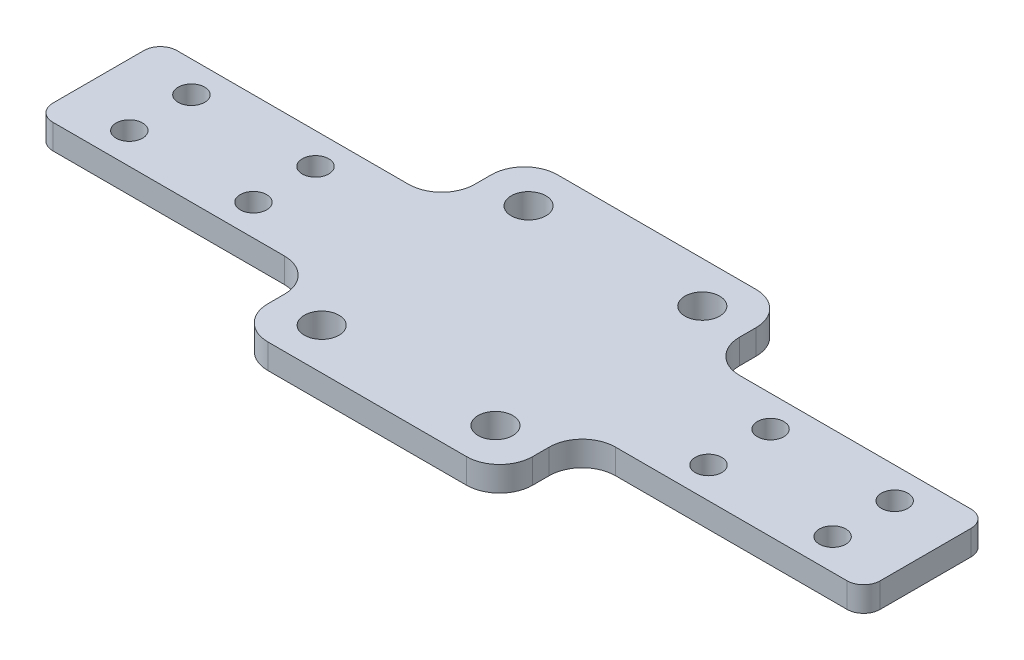
SolidWorks part; units mm, degrees
ref_plane "前视基准面" through (0, 0, 0) normal (0, 0, 1) x (1, 0, 0)
ref_plane "上视基准面" through (0, 0, 0) normal (0, 1, 0) x (1, 0, 0)
ref_plane "右视基准面" through (0, 0, 0) normal (1, 0, 0) x (0, 0, -1)
other "Configuration Table"
sketch "草图1" plane through (0, 0, 0) normal (0, 1, 0) x (1, 0, 0)
  line L1 (-50, -7.5) -> (50, -7.5)
  line L2 (-50, -7.5) -> (-50, 7.5)
  line L3 (-50, 7.5) -> (50, 7.5)
  line L4 (50, -7.5) -> (50, 7.5)
  line L5 (-50, -7.5) -> (50, 7.5) construction
  line L6 (-50, 7.5) -> (50, -7.5) construction
  point P0 (0, 0)
  dimension "D1" = 100
  dimension "D2" = 15
extrude "凸台-拉伸1" add sketch "草图1" along normal blind 3
sketch "草图2" plane through (0, 3, 0) normal (0, 1, 0) x (1, 0, 0)
  line L1 (-16, 17.5) -> (16, 17.5)
  line L2 (-16, 17.5) -> (-16, -17.5)
  line L3 (-16, -17.5) -> (16, -17.5)
  line L4 (16, 17.5) -> (16, -17.5)
  line L5 (0, 0) -> (0, 17.5) construction
  dimension "D1" = 32
  dimension "D2" = 35
  dimension "D3" = 17.5
extrude "凸台-拉伸2" add sketch "草图2" against normal blind 3
sketch "草图3" plane through (0, 3, 0) normal (0, 1, 0) x (1, 0, 0)
  line L0 (0, 0) -> (-50, 0) construction
  line L1 (-16, 7.5) -> (-50, 7.5) construction
  line L2 (0, 0) -> (0, 10) construction
  line L3 (-50, -7.5) -> (-16, -7.5) construction
  line L4 (-35, 7.5) -> (-35, -7.5) construction
  circle A0 centre (-42.5, 3.75) radius 1.6
  circle A1 centre (-42.5, -3.75) radius 1.6
  circle A2 centre (-27.5, -3.75) radius 1.6
  circle A3 centre (-27.5, 3.75) radius 1.6
  circle A4 centre (42.5, -3.75) radius 1.6
  circle A5 centre (42.5, 3.75) radius 1.6
  circle A6 centre (27.5, -3.75) radius 1.6
  circle A7 centre (27.5, 3.75) radius 1.6
  point P4 (-35, 7.5)
  point P26 (-35, -7.5)
  dimension "D2" = 3.2
  dimension "D1" = 35
  dimension "D3" = 3.75
  dimension "D4" = 7.5
  dimension "D5" = 10
extrude "切除-拉伸1" cut sketch "草图3" against normal through all
sketch "草图4" plane through (0, 3, 0) normal (0, 1, 0) x (1, 0, 0)
  line L0 (0, 0) -> (0, 10.9579) construction
  line L1 (0, 0) -> (-19.9516, 0) construction
  circle A0 centre (-10.5, 12.5) radius 2.1
  circle A1 centre (-10.5, -12.5) radius 2.1
  circle A2 centre (10.5, -12.5) radius 2.1
  circle A3 centre (10.5, 12.5) radius 2.1
  dimension "D1" = 4.2
  dimension "D2" = 25
  dimension "D3" = 21
extrude "切除-拉伸2" cut sketch "草图4" against normal through all
fillet "圆角1" radius 4 8 edges at (-16, 1.5, 17.5) (16, 1.5, 17.5) (16, 1.5, -17.5) (-16, 1.5, -17.5) (-16, 1.5, -7.5) (16, 1.5, -7.5) (16, 1.5, 7.5) (-16, 1.5, 7.5)
fillet "圆角2" radius 2 4 edges at (-50, 1.5, 7.5) (-50, 1.5, -7.5) (50, 1.5, 7.5) (50, 1.5, -7.5)
